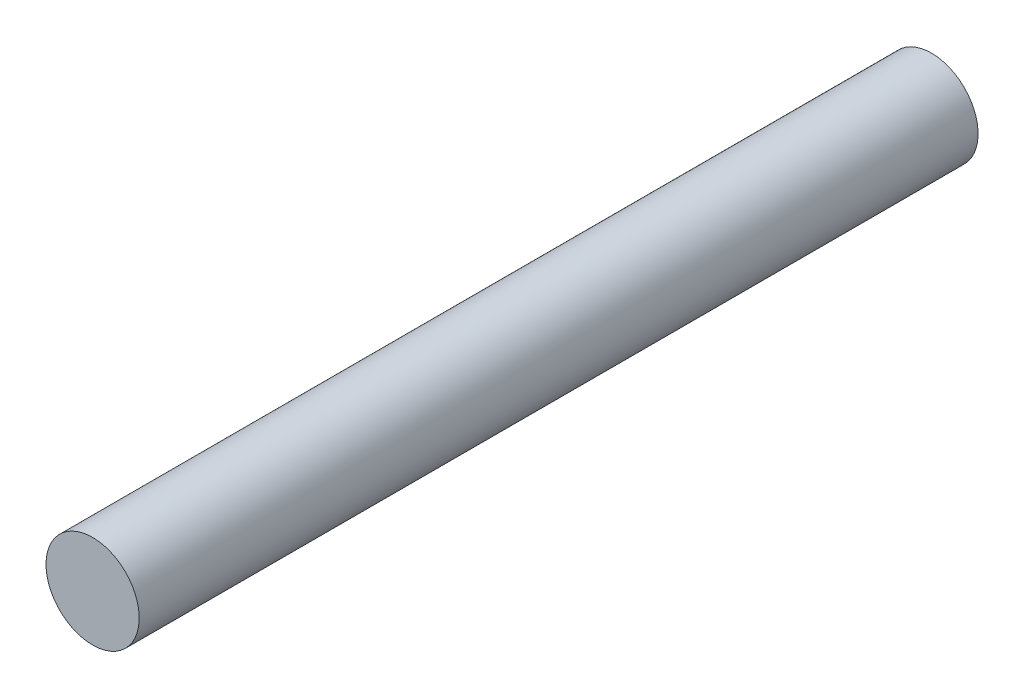
SolidWorks part; units mm, degrees
ref_plane "Ön Düzlem" through (0, 0, 0) normal (0, 0, 1) x (1, 0, 0)
ref_plane "Üst Düzlem" through (0, 0, 0) normal (0, 1, 0) x (1, 0, 0)
ref_plane "Sağ Düzlem" through (0, 0, 0) normal (1, 0, 0) x (0, 0, -1)
sketch "Sketch1" plane through (0, 0, 0) normal (0, 0, 1) x (1, 0, 0)
  circle A0 centre (0, 0) radius 5
  dimension "D1" = 10
extrude "Boss-Extrude1" add sketch "Sketch1" along normal blind 90
